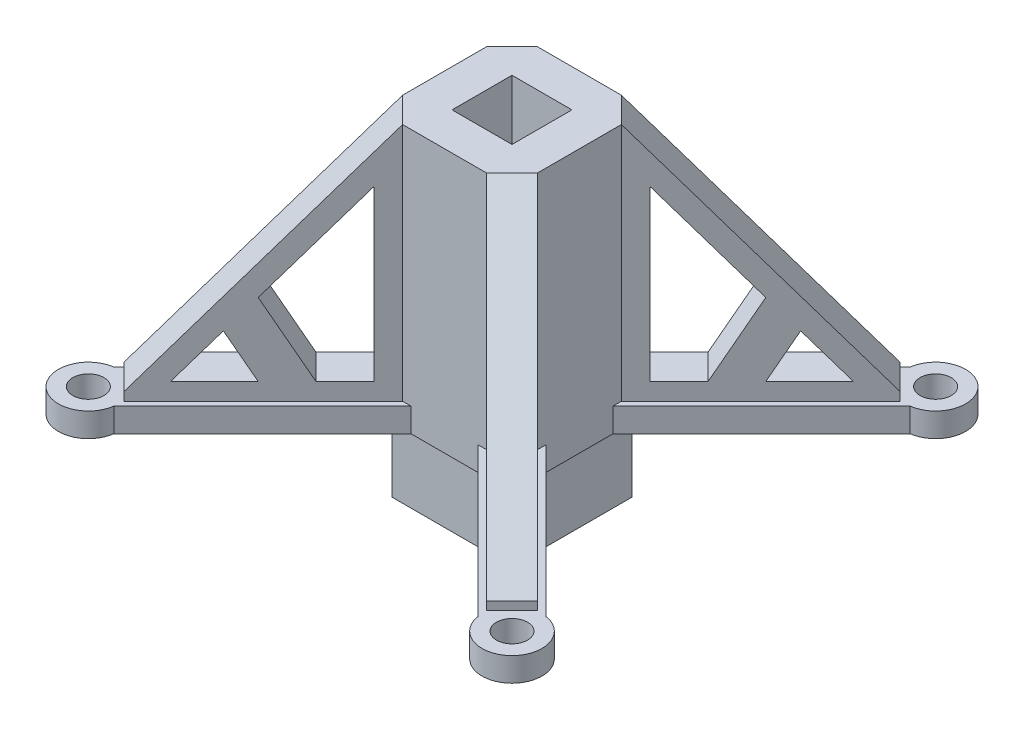
SolidWorks part; units mm, degrees
ref_plane "Front Plane" through (0, 0, 0) normal (0, 0, 1) x (1, 0, 0)
ref_plane "Top Plane" through (0, 0, 0) normal (0, 1, 0) x (1, 0, 0)
ref_plane "Right Plane" through (0, 0, 0) normal (1, 0, 0) x (0, 0, -1)
sketch "Sketch1" plane through (0, 0, 0) normal (0, 1, 0) x (1, 0, 0)
  line L1 (-10, 10) -> (10, 10)
  line L2 (-10, 10) -> (-10, -10)
  line L3 (-10, -10) -> (10, -10)
  line L4 (10, 10) -> (10, -10)
  line L5 (-10, 10) -> (10, -10) construction
  line L6 (-10, -10) -> (10, 10) construction
extrude "Boss-Extrude2" add sketch "Sketch1" against normal blind 12
sketch "Sketch2" plane through (0, 0, 0) normal (0, 1, 0) x (1, 0, 0)
  line L0 (11.25, -5.5931) -> (36.0624, -30.4056)
  line L1 (11.25, 5.5931) -> (36.0624, 30.4056)
  line L2 (5.5931, -11.25) -> (-5.5931, -11.25)
  line L3 (11.25, -5.5931) -> (11.25, 5.5931)
  line L4 (5.5931, 11.25) -> (-5.5931, 11.25)
  line L5 (-11.25, -5.5931) -> (-11.25, 5.5931)
  line L8 (5.5931, 11.25) -> (30.4056, 36.0624)
  line L9 (5.5931, -11.25) -> (30.4056, -36.0624)
  line L10 (-5.5931, -11.25) -> (-30.4056, -36.0624)
  line L11 (-11.25, -5.5931) -> (-36.0624, -30.4056)
  line L12 (-11.25, 5.5931) -> (-36.0624, 30.4056)
  line L13 (-5.5931, 11.25) -> (-30.4056, 36.0624)
  arc A0 (36.0624, 30.4056) -> (30.4056, 36.0624) centre (35.3553, 35.3553) ccw
  arc A1 (30.4056, -36.0624) -> (36.0624, -30.4056) centre (35.3553, -35.3553) ccw
  arc A2 (-36.0624, -30.4056) -> (-30.4056, -36.0624) centre (-35.3553, -35.3553) ccw
  arc A3 (-30.4056, 36.0624) -> (-36.0624, 30.4056) centre (-35.3553, 35.3553) ccw
  point P28 (0, 0)
extrude "Boss-Extrude3" add sketch "Sketch2" along normal blind 4
sketch "Sketch3" plane through (0, 0, 0) normal (0, 1, 0) x (1, 0, 0)
  circle A0 centre (-35.3553, -35.3553) radius 2.6
  circle A1 centre (-35.3553, 35.3553) radius 2.6
  circle A2 centre (35.3553, 35.3553) radius 2.6
  circle A3 centre (35.3553, -35.3553) radius 2.6
  point P12 (0, 0)
extrude "Cut-Extrude1" cut sketch "Sketch3" along normal blind 7
ref_plane "Plane1" through (0, 4, 0) normal (0, 1, 0) x (1, 0, 0)
sketch "Sketch4" plane through (0, 4, 0) normal (0, 1, 0) x (1, 0, 0)
  line L0 (-35.3553, -31.1127) -> (-31.1127, -35.3553)
  line L1 (11.25, 7.0074) -> (35.3553, 31.1127)
  line L2 (7.0074, 11.25) -> (31.1127, 35.3553)
  line L3 (11.25, -7.0074) -> (35.3553, -31.1127)
  line L4 (7.0074, -11.25) -> (31.1127, -35.3553)
  line L5 (-7.0074, -11.25) -> (-31.1127, -35.3553)
  line L6 (-11.25, -7.0074) -> (-35.3553, -31.1127)
  line L7 (-11.25, 7.0074) -> (-35.3553, 31.1127)
  line L8 (-7.0074, 11.25) -> (-31.1127, 35.3553)
  line L13 (-31.1127, 35.3553) -> (-35.3553, 31.1127)
  line L14 (35.3553, 31.1127) -> (31.1127, 35.3553)
  line L15 (31.1127, -35.3553) -> (35.3553, -31.1127)
  line L19 (-7.0074, 11.25) -> (7.0074, 11.25)
  line L20 (-11.25, 7.0074) -> (-11.25, -7.0074)
  line L21 (-7.0074, -11.25) -> (7.0074, -11.25)
  line L22 (11.25, 7.0074) -> (11.25, -7.0074)
  point P13 (0, 0)
  point P23 (0, 0)
  point P25 (0, 0)
  point P29 (0, 0)
  dimension "D1" = 4
extrude "Boss-Extrude4" add sketch "Sketch4" along normal blind 40
move or copy body "Body-Move/Copy1" bodies to move or copy 105 copy no rotation origin (0, 0, 0) rotation axis (0, 1, 0) rotation angle 45
sketch "Sketch6" plane through (0, 0, 0) normal (1, 0, 0) x (0, 0, -1)
  line L0 (-12.9099, 44) -> (-47, 4)
  line L1 (60.5, 4) -> (-60.5, 4) construction
  line L2 (-47, 44) -> (-47, 4) construction
  line L3 (-47, 4) -> (-47, 44)
  line L4 (-47, 44) -> (-12.9099, 44)
  line L5 (0, -12) -> (0, 0) construction
  line L6 (47, 44) -> (12.9099, 44)
  line L7 (47, 4) -> (47, 44)
  line L8 (12.9099, 44) -> (47, 4)
extrude "Cut-Extrude2" cut sketch "Sketch6" against normal blind 40 and the other way blind 40
sketch "Sketch7" plane through (0, 0, 0) normal (0, 0, 1) x (1, 0, 0)
  line L0 (-47, 44) -> (-12.9099, 44)
  line L1 (-12.9099, 44) -> (-47, 4)
  line L2 (60.5, 4) -> (-60.5, 4) construction
  line L3 (-47, 4) -> (-47, 44)
  line L4 (0, -30.8) -> (0, 30.8) construction
  line L5 (47, 4) -> (47, 44)
  line L6 (12.9099, 44) -> (47, 4)
  line L7 (47, 44) -> (12.9099, 44)
extrude "Cut-Extrude3" cut sketch "Sketch7" against normal blind 40 and the other way blind 40
sketch "Sketch8" plane through (0, 0, 0) normal (0, 0, 1) x (1, 0, 0)
  line L1 (60.5, 4) -> (-60.5, 4) construction
  line L2 (-12.9099, 4) -> (-47, 4)
  line L3 (-47, 4) -> (-47, 0) construction
  line L4 (-47, 4) -> (-12.9099, 44)
  line L5 (-16.3169, 9) -> (-16.3169, 6.8574)
  line L6 (-16.3169, 6.8574) -> (-23.1359, 6.8574)
  line L7 (-16.3169, 35.0023) -> (-29.955, 19)
  line L10 (-16.3169, 9) -> (-16.3169, 35.0023)
  line L11 (0, -30.8) -> (0, 30.8) construction
  line L12 (-23.1359, 6.8574) -> (-29.955, 19)
  line L13 (-29.955, 6.8574) -> (-33.8767, 13.8409)
  line L14 (-29.955, 6.8574) -> (-40.3035, 6.8574)
  line L15 (-34.0654, 14.1769) -> (-40.3035, 6.8574)
  line L16 (-33.8767, 13.8409) -> (-34.0654, 14.1769)
  line L17 (33.8767, 13.8409) -> (34.0654, 14.1769)
  line L18 (34.0654, 14.1769) -> (40.3035, 6.8574)
  line L19 (29.955, 6.8574) -> (40.3035, 6.8574)
  line L20 (29.955, 6.8574) -> (33.8767, 13.8409)
  line L21 (23.1359, 6.8574) -> (29.955, 19)
  line L22 (16.3169, 9) -> (16.3169, 35.0023)
  line L23 (16.3169, 35.0023) -> (29.955, 19)
  line L24 (16.3169, 6.8574) -> (23.1359, 6.8574)
  line L25 (16.3169, 9) -> (16.3169, 6.8574)
  line L26 (47, 4) -> (12.9099, 44)
extrude "Cut-Extrude4" cut sketch "Sketch8" against normal blind 40 and the other way blind 40 contours L12 L6 L5 L10 L7 | L13 L16 L15 L14 | L22 L25 L24 L21 L23 | L20 L19 L18 L17
sketch "Sketch9" plane through (0, 0, 0) normal (1, 0, 0) x (0, 0, -1)
  line L1 (0, 30.8) -> (0, -30.8) construction
  line L3 (33.8767, 13.8409) -> (34.0654, 14.1769)
  line L4 (-47, 4) -> (-12.9099, 44)
  line L5 (-16.3169, 9) -> (-16.3169, 6.8574)
  line L6 (-16.3169, 6.8574) -> (-23.1359, 6.8574)
  line L7 (-16.3169, 35.0023) -> (-29.955, 19)
  line L10 (-16.3169, 9) -> (-16.3169, 35.0023)
  line L11 (34.0654, 14.1769) -> (40.3035, 6.8574)
  line L12 (-23.1359, 6.8574) -> (-29.955, 19)
  line L13 (-29.955, 6.8574) -> (-33.8767, 13.8409)
  line L14 (-29.955, 6.8574) -> (-40.3035, 6.8574)
  line L15 (-34.0654, 14.1769) -> (-40.3035, 6.8574)
  line L16 (-33.8767, 13.8409) -> (-34.0654, 14.1769)
  line L17 (29.955, 6.8574) -> (40.3035, 6.8574)
  line L18 (29.955, 6.8574) -> (33.8767, 13.8409)
  line L19 (23.1359, 6.8574) -> (29.955, 19)
  line L20 (16.3169, 9) -> (16.3169, 35.0023)
  line L21 (16.3169, 35.0023) -> (29.955, 19)
  line L22 (16.3169, 6.8574) -> (23.1359, 6.8574)
  line L23 (16.3169, 9) -> (16.3169, 6.8574)
  line L24 (47, 4) -> (12.9099, 44)
extrude "Cut-Extrude7" cut sketch "Sketch9" against normal blind 40 and the other way blind 40 contours L12 L6 L5 L10 L7 | L13 L16 L15 L14 | L20 L23 L22 L19 L21 | L18 L17 L11 L3
ref_plane "Plane3" through (0, 44, 0) normal (0, 1, 0) x (1, 0, 0)
move or copy body "Body-Move/Copy2" bodies to move or copy 110 copy no rotation origin (0, 0, 0) rotation axis (0, 1, 0) rotation angle 45
sketch "Sketch11" plane through (0, 44, 0) normal (0, 1, 0) x (1, 0, 0)
  line L1 (-5, 5) -> (5, 5)
  line L2 (-5, 5) -> (-5, -5)
  line L3 (-5, -5) -> (5, -5)
  line L4 (5, 5) -> (5, -5)
  line L5 (-5, 5) -> (5, -5) construction
  line L6 (-5, -5) -> (5, 5) construction
  point P0 (0, 0)
extrude "Cut-Extrude8" cut sketch "Sketch11" against normal blind 10
sketch "Sketch12" plane through (0, 4, 0) normal (0, 1, 0) x (1, 0, 0)
  line L0 (-35.3553, -31.1127) -> (-31.1127, -35.3553)
  line L1 (-31.1127, -35.3553) -> (-30.2642, -34.5068)
  line L2 (-31.1127, -35.3553) -> (-7.0074, -11.25) construction
  line L3 (-30.2642, -34.5068) -> (-34.5068, -30.2642)
  line L4 (-11.25, -7.0074) -> (-35.3553, -31.1127) construction
  line L5 (-34.5068, -30.2642) -> (-35.3553, -31.1127)
  line L6 (-30.2642, 34.5068) -> (-31.1127, 35.3553)
  line L7 (-34.5068, 30.2642) -> (-30.2642, 34.5068)
  line L8 (-31.1127, 35.3553) -> (-35.3553, 31.1127)
  line L9 (-35.3553, 31.1127) -> (-34.5068, 30.2642)
  line L10 (34.5068, 30.2642) -> (35.3553, 31.1127)
  line L11 (30.2642, 34.5068) -> (34.5068, 30.2642)
  line L12 (35.3553, 31.1127) -> (31.1127, 35.3553)
  line L13 (31.1127, 35.3553) -> (30.2642, 34.5068)
  line L14 (30.2642, -34.5068) -> (31.1127, -35.3553)
  line L15 (34.5068, -30.2642) -> (30.2642, -34.5068)
  line L16 (31.1127, -35.3553) -> (35.3553, -31.1127)
  line L17 (35.3553, -31.1127) -> (34.5068, -30.2642)
  point P25 (0, 0)
  dimension "D1" = 4
extrude "Cut-Extrude9" cut sketch "Sketch12" along normal blind 17
